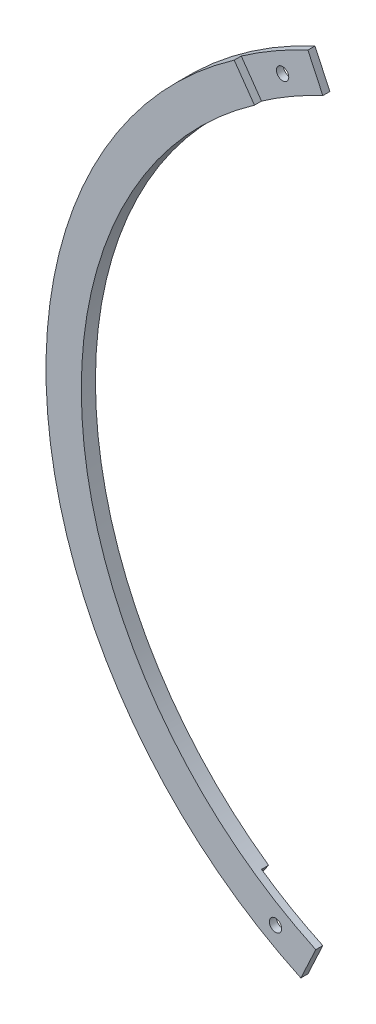
SolidWorks part; units mm, degrees
ref_plane "Plan de face" through (0, 0, 0) normal (0, 0, 1) x (1, 0, 0)
ref_plane "Plan de dessus" through (0, 0, 0) normal (0, 1, 0) x (1, 0, 0)
ref_plane "Plan de droite" through (0, 0, 0) normal (1, 0, 0) x (0, 0, -1)
sketch "Esquisse1" plane through (0, 0, 0) normal (0, 0, 1) x (1, 0, 0)
  line L1 (-120, 0) -> (-130, 0) construction
  line L6 (-130, 0) -> (0, 0) construction
  line L7 (-48.6011, -104.2254) -> (-52.8273, -113.2885)
  line L8 (-48.6011, 104.2254) -> (-52.8273, 113.2885)
  line L9 (0, 0) -> (-48.6011, 104.2254) construction
  line L10 (0, 0) -> (-48.6011, -104.2254) construction
  arc A0 (-52.8273, 113.2885) -> (-125, 0) centre (0, 0) ccw
  arc A1 (-48.6011, 104.2254) -> (-48.6011, -104.2254) centre (0, 0) ccw
  arc A2 (-125, 0) -> (-52.8273, -113.2885) centre (0, 0) ccw
  dimension "D5" = 125
  dimension "D6" = 115
  dimension "D1" = 120
  dimension "D3" = 10
  dimension "D7" = 65
  dimension "D8" = 65
extrude "Boss.-Extru.1" add sketch "Esquisse1" along normal blind 4
sketch "Esquisse3" plane through (0, 0, 4) normal (0, 0, 1) x (1, 0, 0)
  line L0 (-60, 103.923) -> (0, 0) construction
  line L1 (0, 0) -> (-60, -103.923) construction
  line L2 (-52.8273, 113.2885) -> (0, 0) construction
  circle A0 centre (-60, 103.923) radius 1.75
  circle A1 centre (-60, -103.923) radius 1.75
  dimension "D1" = 3.5
  dimension "D2" = 120
  dimension "D3" = 5
  dimension "D4" = 120
extrude "Enlèv. mat.-Extru.1" cut sketch "Esquisse3" against normal blind 10
sketch "Esquisse4" plane through (0, 0, 4) normal (0, 0, 1) x (1, 0, 0)
  line L0 (-71.6971, 102.394) -> (-65.9613, 94.2025)
  line L1 (-52.8273, 113.2885) -> (-48.6011, 104.2254)
  line L2 (-48.6011, 104.2254) -> (-52.8273, 113.2885) construction
  line L3 (-65.9613, 94.2025) -> (0, 0) construction
  arc A0 (-48.6011, 104.2254) -> (-65.9613, 94.2025) centre (0, 0) ccw
  arc A1 (-71.6971, 102.394) -> (-52.8273, 113.2885) centre (0, 0) cw
  arc A2 (-52.8273, 113.2885) -> (-52.8273, -113.2885) centre (0, 0) ccw construction
  dimension "D1" = 10
extrude "Enlèv. mat.-Extru.2" cut sketch "Esquisse4" against normal blind 2
sketch "Esquisse6" plane through (0, 0, 0) normal (0, 0, -1) x (-1, 0, 0)
  line L0 (65.9613, -94.2025) -> (71.6971, -102.394)
  line L1 (48.6011, -104.2254) -> (52.8273, -113.2885)
  line L2 (52.8273, -113.2885) -> (48.6011, -104.2254) construction
  line L3 (65.9613, -94.2025) -> (0, 0) construction
  arc A0 (65.9613, -94.2025) -> (48.6011, -104.2254) centre (0, 0) cw
  arc A1 (71.6971, -102.394) -> (52.8273, -113.2885) centre (0, 0) cw
  dimension "D1" = 10
extrude "Enlèv. mat.-Extru.3" cut sketch "Esquisse6" against normal blind 2
